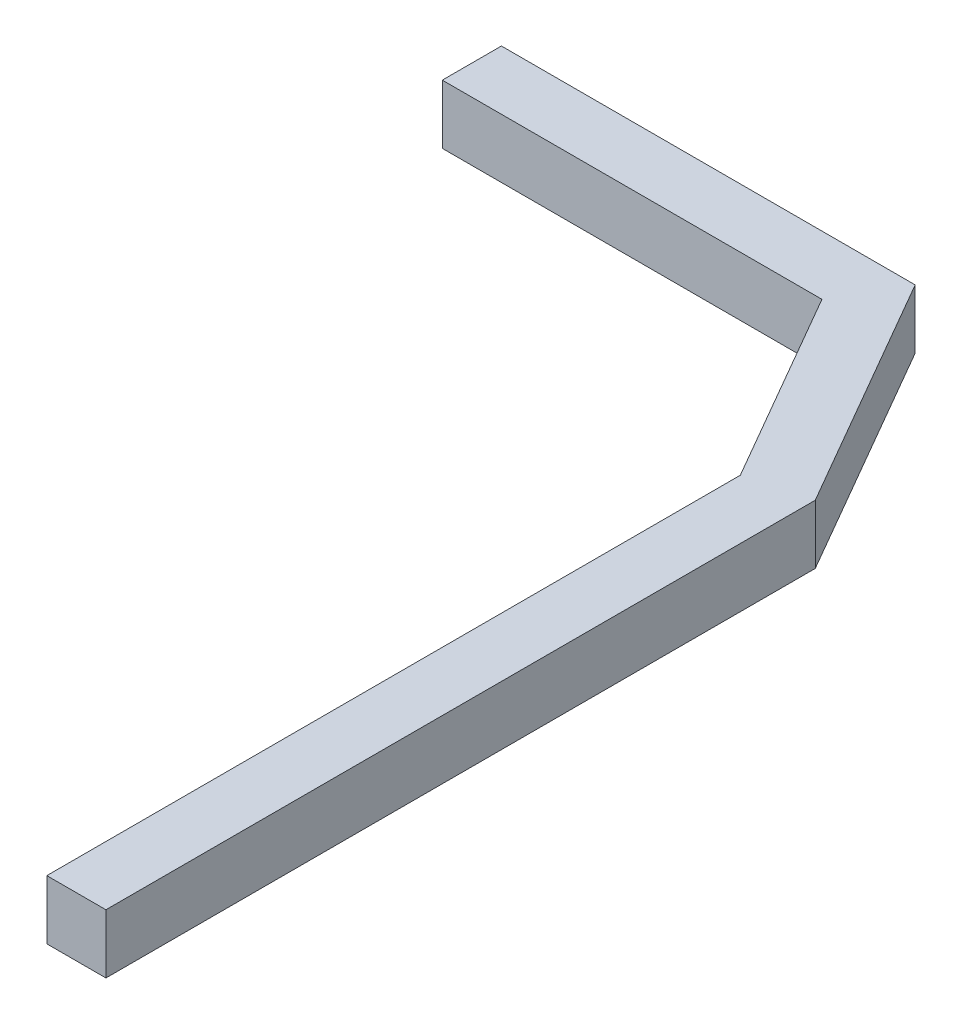
SolidWorks part; units mm, degrees
material "Polylactic Acid"
ref_plane "Top Plane" through (0, 0, 0) normal (0, 0, 1) x (1, 0, 0)
ref_plane "Right Plane" through (0, 0, 0) normal (0, 1, 0) x (1, 0, 0)
ref_plane "Front Plane" through (0, 0, 0) normal (1, 0, 0) x (0, 0, -1)
sketch "Sketch1" plane through (0, 0, 0) normal (0, 1, 0) x (1, 0, 0)
  line L0 (-41.547, 80) -> (-41.547, 75)
  line L1 (-41.547, 75) -> (-9.4338, 75)
  line L2 (-9.4338, 75) -> (0, 58.6603)
  line L3 (0, 58.6603) -> (0, 0)
  line L4 (0, 0) -> (5, 0)
  line L5 (5, 0) -> (5, 60)
  line L6 (5, 60) -> (-6.547, 80)
  line L7 (-6.547, 80) -> (-41.547, 80)
  point P2 (0, 0)
  dimension "D1" = 5
  dimension "D2" = 35
  dimension "D3" = 150
  dimension "D4" = 5
  dimension "D5" = 20
  dimension "D6" = 60
extrude "Boss-Extrude1" add sketch "Sketch1" along normal mid plane 5
equation "\"D4@Sketch1\"=\"D1@Sketch1\""
